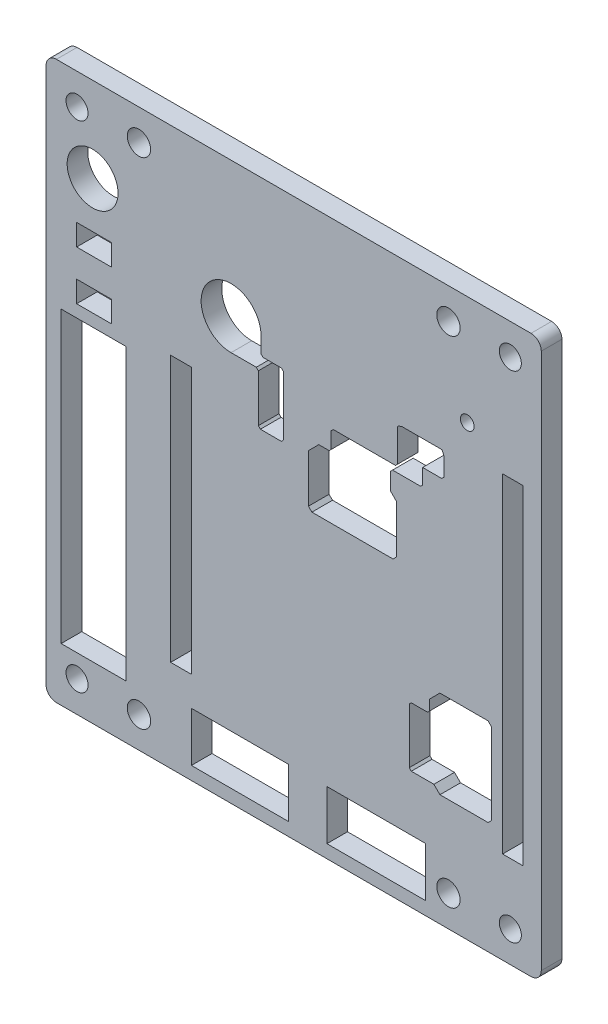
SolidWorks part; units mm, degrees
ref_plane "Alzado" through (0, 0, 0) normal (0, 0, 1) x (1, 0, 0)
ref_plane "Planta" through (0, 0, 0) normal (0, 1, 0) x (1, 0, 0)
ref_plane "Vista lateral" through (0, 0, 0) normal (1, 0, 0) x (0, 0, -1)
sketch "Model" plane through (0, 0, 0) normal (0, 0, 1) x (1, 0, 0)
  line L0 (79.0698, 220.6038) -> (79.0698, 298.6084)
  line L1 (7.0674, 298.6084) -> (7.0674, 220.6038)
  line L2 (8.5674, 219.1038) -> (77.5698, 219.1038)
  line L3 (77.5698, 300.1084) -> (8.5674, 300.1084)
  line L4 (76.4432, 280.3563) -> (73.4432, 280.3563)
  line L5 (76.4432, 232.4763) -> (76.4432, 280.3563)
  line L6 (73.4432, 232.4763) -> (76.4432, 232.4763)
  line L7 (73.4432, 280.3563) -> (73.4432, 232.4763)
  line L8 (28.1808, 232.4801) -> (28.1808, 271.1578)
  line L9 (25.1808, 232.4801) -> (28.1808, 232.4801)
  line L10 (25.1808, 271.1578) -> (25.1808, 232.4801)
  line L11 (9.2551, 269.0104) -> (9.2563, 226.8832)
  line L12 (18.685, 269.0104) -> (18.6863, 226.8832)
  line L13 (18.685, 269.0104) -> (9.2551, 269.0104)
  line L14 (18.6863, 226.8832) -> (9.2563, 226.8832)
  line L15 (37.929, 268.6584) -> (37.9301, 275.5694)
  line L16 (41.2725, 268.3584) -> (38.2289, 268.3584)
  line L17 (41.5725, 277.3009) -> (41.5725, 268.6584)
  line L18 (38.6121, 277.6009) -> (41.2725, 277.6009)
  line L19 (47.8995, 221.0056) -> (62.2048, 221.0056)
  line L20 (62.2048, 228.2055) -> (47.8995, 228.2055)
  line L21 (47.8995, 228.2055) -> (47.8995, 221.0056)
  line L22 (62.2048, 221.0056) -> (62.2048, 228.2055)
  line L23 (28.1941, 221.0056) -> (42.2994, 221.0056)
  line L24 (42.2994, 228.2055) -> (28.1941, 228.2055)
  line L25 (28.1941, 228.2055) -> (28.1941, 221.0056)
  line L26 (42.2994, 221.0056) -> (42.2994, 228.2055)
  line L27 (16.6077, 273.8998) -> (11.5077, 273.8998)
  line L28 (16.6077, 270.7998) -> (16.6077, 273.8998)
  line L29 (11.5077, 270.7998) -> (16.6077, 270.7998)
  line L30 (11.5077, 273.8998) -> (11.5077, 270.7998)
  line L31 (16.6077, 281.0451) -> (11.5077, 281.0451)
  line L32 (16.6077, 277.9451) -> (16.6077, 281.0451)
  line L33 (11.5077, 277.9451) -> (16.6077, 277.9451)
  line L34 (11.5077, 281.0451) -> (11.5077, 277.9451)
  line L35 (25.1808, 271.1578) -> (28.1808, 271.1578)
  line L36 (45.2171, 262.1628) -> (45.7171, 261.6628)
  line L37 (57.5171, 261.6628) -> (58.0171, 262.1628)
  line L38 (45.2171, 269.1628) -> (46.7171, 270.6628)
  line L39 (48.226, 270.6628) -> (46.7171, 270.6628)
  line L40 (45.2171, 269.1628) -> (45.2171, 262.1628)
  line L41 (58.0171, 262.1628) -> (58.0171, 269.1628)
  line L42 (45.7171, 261.6628) -> (57.5171, 261.6628)
  line L43 (57.8731, 273.6225) -> (48.826, 273.6225)
  line L44 (57.1392, 270.0406) -> (57.1392, 272.5218)
  line L45 (48.526, 270.9628) -> (48.526, 273.3225)
  line L46 (48.526, 270.9628) -> (48.226, 270.6628)
  line L47 (48.826, 273.6225) -> (48.526, 273.3225)
  line L48 (58.0171, 269.1628) -> (57.1392, 270.0406)
  line L49 (63.4541, 236.2651) -> (60.1723, 236.2651)
  line L50 (58.1732, 273.9225) -> (58.1739, 278.6843)
  line L51 (61.5165, 272.8218) -> (57.4392, 272.8218)
  line L52 (61.8165, 275.3409) -> (61.8165, 273.1218)
  line L53 (58.774, 278.9843) -> (64.597, 278.9843)
  line L54 (71.3319, 235.3872) -> (64.3319, 235.3872)
  line L55 (71.3319, 248.1872) -> (71.8319, 247.6872)
  line L56 (71.8319, 235.8872) -> (71.3319, 235.3872)
  line L57 (64.3319, 248.1872) -> (62.8319, 246.6872)
  line L58 (62.8319, 245.1782) -> (62.8319, 246.6872)
  line L59 (64.3319, 248.1872) -> (71.3319, 248.1872)
  line L60 (71.8319, 247.6872) -> (71.8319, 235.8872)
  line L61 (59.8723, 236.5651) -> (59.8723, 244.5782)
  line L63 (62.5319, 244.8782) -> (60.1723, 244.8782)
  line L64 (62.5319, 244.8782) -> (62.8319, 245.1782)
  line L65 (59.8723, 244.5782) -> (60.1723, 244.8782)
  line L66 (64.3319, 235.3872) -> (63.4541, 236.2651)
  line L68 (59.8723, 236.5651) -> (60.1723, 236.2651)
  line L69 (41.5725, 277.3009) -> (41.2725, 277.6009)
  line L70 (41.5725, 268.6584) -> (41.2725, 268.3584)
  line L71 (38.2289, 268.3584) -> (37.929, 268.6584)
  line L72 (58.1739, 278.6843) -> (58.2618, 278.7722)
  line L73 (58.2618, 278.7722) -> (58.774, 278.9843)
  line L74 (61.5165, 272.8218) -> (61.8165, 273.1218)
  line L75 (33.9621, 275.8694) -> (37.6301, 275.8694)
  line L76 (38.3121, 280.2194) -> (38.3121, 277.9009)
  line L77 (38.3121, 277.9009) -> (38.6121, 277.6009)
  line L78 (37.6301, 275.8694) -> (37.9301, 275.5694)
  line L79 (57.8731, 273.6225) -> (58.1732, 273.9225)
  line L80 (57.4392, 272.8218) -> (57.1392, 272.5218)
  line L81 (64.5978, 275.3409) -> (61.8165, 275.3409)
  line L82 (64.8978, 278.3835) -> (64.8978, 275.6409)
  line L83 (64.597, 278.9843) -> (64.6856, 278.8956)
  line L84 (64.6856, 278.8956) -> (64.8978, 278.3835)
  line L85 (64.8978, 275.6409) -> (64.5978, 275.3409)
  arc A0 (8.5674, 300.1084) -> (7.0674, 298.6084) centre (8.5674, 298.6084) ccw
  arc A1 (7.0674, 220.6038) -> (8.5674, 219.1038) centre (8.5674, 220.6038) ccw
  arc A2 (77.5698, 219.1038) -> (79.0698, 220.6038) centre (77.5698, 220.6038) ccw
  arc A3 (79.0698, 298.6084) -> (77.5698, 300.1084) centre (77.5698, 298.6084) ccw
  circle A4 centre (68.3041, 284.2311) radius 1
  circle A5 centre (13.8303, 287.7239) radius 3.7
  circle A6 centre (20.5667, 223.6035) radius 1.7
  circle A7 centre (65.5701, 223.6035) radius 1.7
  circle A8 centre (11.5671, 223.6035) radius 1.6003
  circle A9 centre (74.5698, 223.6035) radius 1.6003
  circle A10 centre (20.5667, 295.6084) radius 1.7
  circle A11 centre (65.5701, 295.6084) radius 1.7
  circle A12 centre (74.5698, 295.6084) radius 1.6003
  circle A13 centre (11.5671, 295.6084) radius 1.6003
  arc A14 (38.3121, 280.2194) -> (33.9621, 275.8694) centre (33.9621, 280.2194) ccw
extrude "Saliente-Extruir1" add sketch "Model" along normal blind 3
